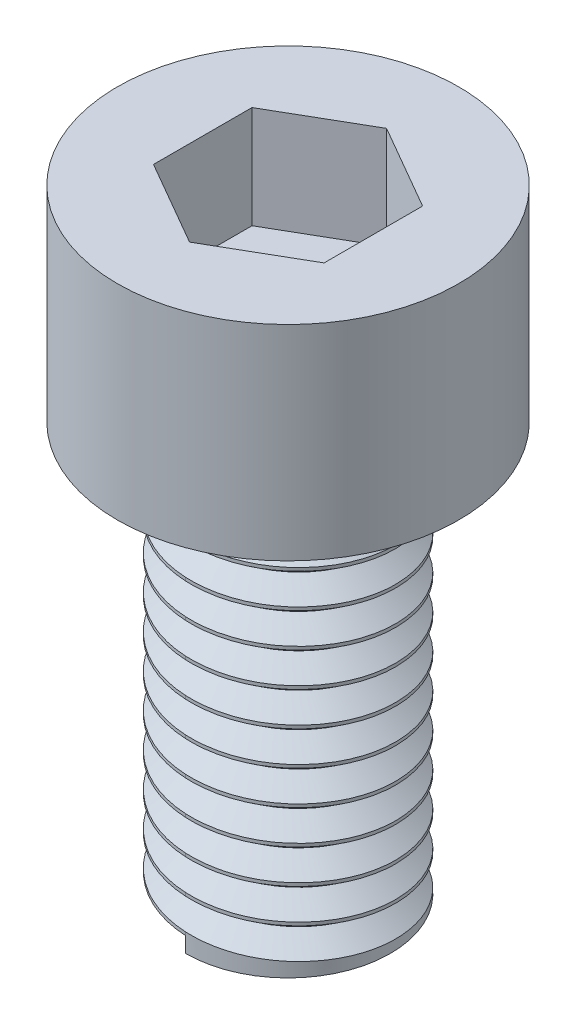
SolidWorks part; units mm, degrees
material "Acero aleado"
ref_plane "Alzado" through (0, 0, 0) normal (0, 0, 1) x (1, 0, 0)
ref_plane "Planta" through (0, 0, 0) normal (0, 1, 0) x (1, 0, 0)
ref_plane "Vista lateral" through (0, 0, 0) normal (1, 0, 0) x (0, 0, -1)
sketch "Sk_Cabeza" plane through (0, 0, 0) normal (0, 1, 0) x (1, 0, 0)
  circle A0 centre (0, 0) radius 5
  dimension "DIAM1" = 10
extrude "Cabeza" add sketch "Sk_Cabeza" along normal blind 6 from offset 0
sketch "Sk_Cana" plane through (0, 0, 0) normal (0, 1, 0) x (1, 0, 0)
  circle A0 centre (0, 0) radius 3
  dimension "DIAM2" = 6
extrude "Cana" add sketch "Sk_Cana" along normal blind 12 from offset 12
ref_plane "Plano_cabeza" through (0, 6, 0) normal (0, 1, 0) x (1, 0, 0)
sketch "Sk_Hueco_Allen" plane through (0, 6, 0) normal (0, 1, 0) x (1, 0, 0)
  line L0 (2.5, -1.4434) -> (0, -2.8868)
  line L1 (0, -2.8868) -> (-2.5, -1.4434)
  line L2 (-2.5, -1.4434) -> (-2.5, 1.4434)
  line L3 (-2.5, 1.4434) -> (0, 2.8868)
  line L4 (0, 2.8868) -> (2.5, 1.4434)
  line L5 (2.5, 1.4434) -> (2.5, -1.4434)
extrude "Hueco_Allen" cut sketch "Sk_Hueco_Allen" against normal blind 3
ref_plane "Plano_punta" through (0, -12, 0) normal (0, 1, 0) x (1, 0, 0)
sketch "Sk_Helice" plane through (0, -12, 0) normal (0, 1, 0) x (1, 0, 0)
  circle A0 centre (0, 0) radius 3
curve "Helice_rosca" pitch 1 height 11.4 turns 11.4
sketch "Sk_Perfil_rosca" plane through (0, 0, 0) normal (1, 0, 0) x (0, 0, -1)
  line L0 (-3.2, -12.6) -> (-2.3866, -12)
  line L1 (-2.3866, -12) -> (-3.2, -11.4)
  line L2 (-3.2, -11.4) -> (-3.2, -12.6)
sweep "Rosca_M6x1,0" cut profiles "Sk_Perfil_rosca" path "Helice_rosca"
